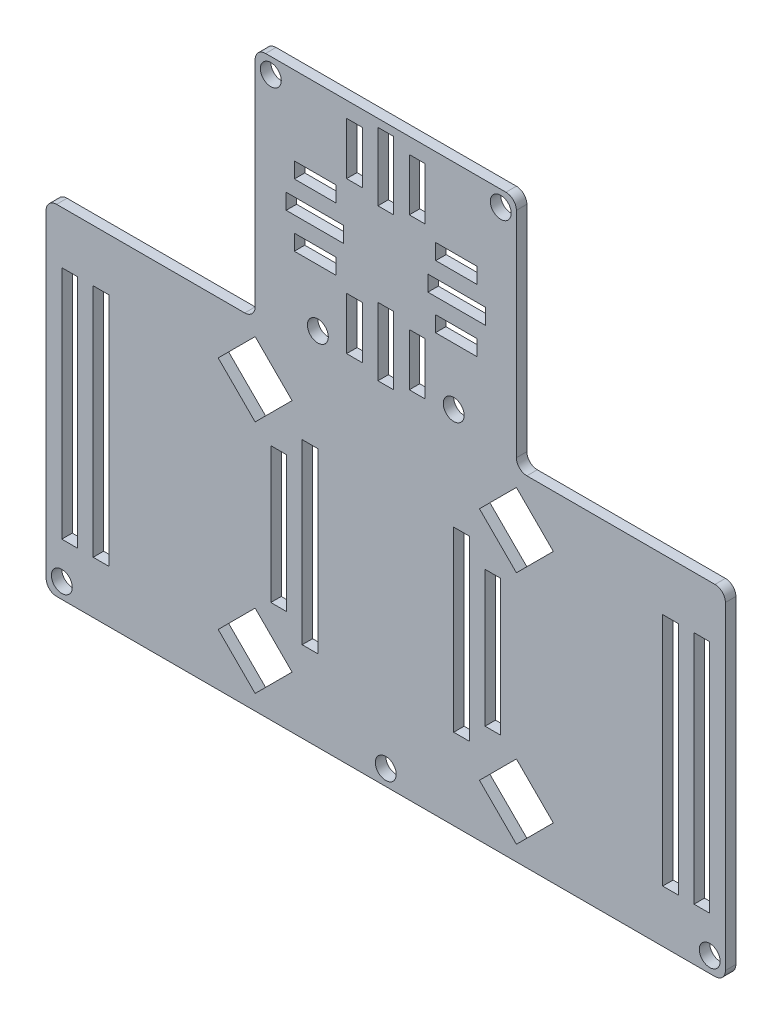
SolidWorks part; units mm, degrees
ref_plane "Front Plane" through (0, 0, 0) normal (0, 0, 1) x (1, 0, 0)
ref_plane "Top Plane" through (0, 0, 0) normal (0, 1, 0) x (1, 0, 0)
ref_plane "Right Plane" through (0, 0, 0) normal (1, 0, 0) x (0, 0, -1)
sketch "Sketch1" plane through (0, 0, 0) normal (0, 0, 1) x (1, 0, 0)
  line L1 (65, -32.5) -> (-65, -32.5)
  line L2 (65, -32.5) -> (65, 32.5)
  line L3 (65, 32.5) -> (-65, 32.5)
  line L4 (-65, -32.5) -> (-65, 32.5)
  line L5 (65, -32.5) -> (-65, 32.5) construction
  line L6 (65, 32.5) -> (-65, -32.5) construction
  line L7 (25, -12.5) -> (-25, -12.5)
  line L8 (25, -12.5) -> (25, 77.5)
  line L9 (25, 77.5) -> (-25, 77.5)
  line L10 (-25, -12.5) -> (-25, 77.5)
  line L11 (25, -12.5) -> (-25, 77.5) construction
  line L12 (25, 77.5) -> (-25, -12.5) construction
  point P0 (0, 0)
  point P6 (0, 32.5)
extrude "Boss-Extrude1" add sketch "Sketch1" along normal blind 2 contours L7 L10 L3 L4 L1 L2 L8 | L10 L3 L8 L9 | L10 L7 L8 L3
fillet "Fillet1" radius 2 8 edges at (25, 77.5, 1) (65, -32.5, 1) (65, 32.5, 1) (25, 32.5, 1) (-25, 32.5, 1) (-25, 77.5, 1) (-65, 32.5, 1) (-65, -32.5, 1)
sketch "Sketch3" plane through (0, 0, 0) normal (0, 0, -1) x (-1, 0, 0)
  line L0 (0, -32.5) -> (0, 77.5)
  line L1 (25, 55) -> (-25, 55)
  line L2 (-62, 0) -> (-62, 22.5)
  line L3 (-62, 0) -> (-62, -22.5)
  line L4 (-62, -22.5) -> (-59, -22.5)
  line L5 (-59, -22.5) -> (-59, 22.5)
  line L6 (-59, 22.5) -> (-62, 22.5)
  line L7 (-13, -17) -> (-16, -17)
  line L8 (-56, 22.5) -> (-56, -22.5)
  line L9 (-16, -17) -> (-16, 13)
  line L10 (-56, -22.5) -> (-53, -22.5)
  line L11 (-53, -22.5) -> (-53, 22.5)
  line L12 (-53, 22.5) -> (-56, 22.5)
  line L13 (-63, -32.5) -> (63, -32.5) construction
  line L14 (-23, 77.5) -> (23, 77.5) construction
  line L15 (65, -30.5) -> (65, 30.5) construction
  line L16 (65, 22.5) -> (65, -22.5)
  line L17 (25, 34.5) -> (25, 75.5) construction
  line L18 (-25, -15.4289) -> (-32.0711, -22.5)
  line L19 (-32.0711, -22.5) -> (-25, -29.5711)
  line L20 (-25, -29.5711) -> (-17.9289, -22.5)
  line L21 (-25, 34.5) -> (-25, 75.5) construction
  line L22 (-1.5, 45.5) -> (-1.5, 47)
  line L23 (-1.5, 35.5) -> (-1.5, 34)
  line L24 (-17.9289, -22.5) -> (-25, -15.4289)
  line L25 (-25, 29.5711) -> (-32.0711, 22.5)
  line L26 (-32.0711, 22.5) -> (-25, 15.4289)
  line L27 (-25, 15.4289) -> (-17.9289, 22.5)
  line L28 (-17.9289, 22.5) -> (-25, 29.5711)
  line L29 (-25, 0) -> (-22, 0)
  line L30 (-22, 0) -> (-22, 13)
  line L31 (-22, 0) -> (-22, -13)
  line L32 (-22, -13) -> (-19, -13)
  line L33 (-19, -13) -> (-19, 13)
  line L34 (-19, 13) -> (-22, 13)
  line L35 (-1.5, 34) -> (1.5, 34)
  line L36 (-16, 13) -> (-16, 17)
  line L37 (-16, 17) -> (-13, 17)
  line L38 (-13, 17) -> (-13, -17)
  line L39 (-1.5, 45.5) -> (-1.5, 35.5)
  line L40 (-1.5, 47) -> (1.5, 47)
  line L41 (-4.5, 45.5) -> (-7.5, 45.5)
  line L42 (-7.5, 35.5) -> (-4.5, 35.5)
  line L43 (-8.0637, 56.4704) -> (-8.0637, 53.4704)
  line L44 (-19.0637, 56.4704) -> (-8.0637, 56.4704)
  line L45 (-19.0637, 53.4704) -> (-8.0637, 53.4704)
  line L46 (-19.0637, 53.4704) -> (-19.0637, 56.4704)
  line L47 (-7.5, 45.5) -> (-7.5, 35.5)
  line L48 (-4.5, 45.5) -> (-4.5, 35.5)
  line L49 (-9.5637, 59.4484) -> (-17.5, 59.4484)
  line L50 (7.5, 74.5) -> (4.5, 74.5)
  line L51 (-17.5, 59.4484) -> (-17.5, 62.4484)
  line L52 (-17.5, 62.4484) -> (-9.5637, 62.4484)
  line L53 (-9.5637, 62.4484) -> (-9.5637, 59.4484)
  line L54 (7.5, 64.5) -> (7.5, 74.5)
  line L55 (-9.5087, 50.4704) -> (-17.5, 50.4704)
  line L56 (-17.5, 50.4704) -> (-17.5, 47.4704)
  line L57 (-17.5, 47.4704) -> (-9.5087, 47.4704)
  line L58 (-9.5087, 47.4704) -> (-9.5087, 50.4704)
  line L59 (1.5, 74.5) -> (1.5, 76)
  line L60 (-4.5, 64.5) -> (-7.5, 64.5)
  line L61 (-4.5, 64.5) -> (-4.5, 74.5)
  line L62 (1.5, 64.5) -> (1.5, 63)
  line L63 (1.5, 64.5) -> (1.5, 74.5)
  line L64 (-1.5, 64.5) -> (-1.5, 74.5)
  line L65 (-1.5, 64.5) -> (-1.5, 63)
  line L66 (-1.5, 74.5) -> (-1.5, 76)
  line L67 (-1.5, 63) -> (1.5, 63)
  line L68 (-1.5, 76) -> (1.5, 76)
  line L69 (-7.5, 64.5) -> (-7.5, 74.5)
  line L70 (-7.5, 74.5) -> (-4.5, 74.5)
  line L71 (4.5, 64.5) -> (4.5, 74.5)
  line L72 (4.5, 64.5) -> (7.5, 64.5)
  line L73 (9.5087, 47.4704) -> (9.5087, 50.4704)
  line L74 (17.5, 47.4704) -> (9.5087, 47.4704)
  line L75 (17.5, 50.4704) -> (17.5, 47.4704)
  line L76 (9.5087, 50.4704) -> (17.5, 50.4704)
  line L77 (9.5637, 62.4484) -> (9.5637, 59.4484)
  line L78 (17.5, 62.4484) -> (9.5637, 62.4484)
  line L79 (17.5, 59.4484) -> (17.5, 62.4484)
  line L80 (9.5637, 59.4484) -> (17.5, 59.4484)
  line L81 (4.5, 45.5) -> (4.5, 35.5)
  line L82 (7.5, 45.5) -> (7.5, 35.5)
  line L83 (19.0637, 53.4704) -> (8.0637, 53.4704)
  line L84 (19.0637, 56.4704) -> (8.0637, 56.4704)
  line L85 (8.0637, 56.4704) -> (8.0637, 53.4704)
  line L86 (7.5, 35.5) -> (4.5, 35.5)
  line L87 (4.5, 45.5) -> (7.5, 45.5)
  line L88 (1.5, 45.5) -> (1.5, 35.5)
  line L89 (1.5, 35.5) -> (1.5, 34)
  line L90 (1.5, 45.5) -> (1.5, 47)
  line L91 (13, 17) -> (13, -17)
  line L92 (16, 17) -> (13, 17)
  line L93 (16, 13) -> (16, 17)
  line L94 (19, 13) -> (22, 13)
  line L95 (19, -13) -> (19, 13)
  line L96 (22, -13) -> (19, -13)
  line L97 (22, 0) -> (22, -13)
  line L98 (22, 0) -> (22, 13)
  line L99 (25, 0) -> (22, 0)
  line L100 (17.9289, 22.5) -> (25, 29.5711)
  line L101 (25, 15.4289) -> (17.9289, 22.5)
  line L102 (32.0711, 22.5) -> (25, 15.4289)
  line L103 (25, 29.5711) -> (32.0711, 22.5)
  line L104 (17.9289, -22.5) -> (25, -15.4289)
  line L105 (25, -29.5711) -> (17.9289, -22.5)
  line L106 (32.0711, -22.5) -> (25, -29.5711)
  line L107 (25, -15.4289) -> (32.0711, -22.5)
  line L108 (53, 22.5) -> (56, 22.5)
  line L109 (53, -22.5) -> (53, 22.5)
  line L110 (56, -22.5) -> (53, -22.5)
  line L111 (16, -17) -> (16, 13)
  line L112 (56, 22.5) -> (56, -22.5)
  line L113 (13, -17) -> (16, -17)
  line L114 (59, 22.5) -> (62, 22.5)
  line L115 (59, -22.5) -> (59, 22.5)
  line L116 (62, -22.5) -> (59, -22.5)
  line L117 (62, 0) -> (62, -22.5)
  line L118 (62, 0) -> (62, 22.5)
  line L119 (19.0637, 53.4704) -> (19.0637, 56.4704)
  point P66 (0, 76)
  point P74 (0, 63)
  point P102 (0, 47)
  point P105 (0, 34)
extrude "Cut-Extrude1" cut sketch "Sketch3" against normal blind 2 contours L87 L81 L86 L82 | L48 L41 L47 L42 | L40 L22 L39 L23 L35 L0 | L88 L90 L40 L0 L35 L89 | L70 L69 L60 L61 | L68 L66 L64 L65 L67 L0 | L68 L0 L67 L62 L63 L59 | L71 L72 L54 L50 | L77 L80 L79 L78 | L1 L119 L84 L85 | L83 L119 L1 L85 | L76 L73 L74 L75 | L53 L52 L51 L49 | L46 L1 L43 L44 | L46 L45 L43 L1 | L57 L58 L55 L56 | L27 L28 L25 L26 | L33 L34 L30 L31 L32 | L38 L37 L36 L9 L7 | L20 L24 L18 L19 | L11 L12 L8 L10 | L5 L6 L2 L3 L4 | L103 L100 L101 L102 | L97 L98 L94 L95 L96 | L91 L113 L111 L93 L92 | L107 L104 L105 L106 | L117 L118 L114 L115 L116 | L112 L108 L109 L110
sketch "Sketch4" plane through (0, 0, 2) normal (0, 0, 1) x (1, 0, 0)
  line L0 (0, -32.5) -> (0, -29.5)
  line L1 (63, -32.5) -> (-63, -32.5) construction
  line L2 (0, -29.5) -> (0, 36.5)
  line L3 (0, 36.5) -> (13, 36.5)
  line L4 (0, 36.5) -> (-13, 36.5)
  line L5 (0, -29.5) -> (-62, -29.5)
  line L6 (0, -29.5) -> (62, -29.5)
  line L7 (0, 77.5) -> (0, 74.5)
  line L8 (23, 77.5) -> (-23, 77.5) construction
  line L9 (0, 74.5) -> (22, 74.5)
  line L10 (0, 74.5) -> (-22, 74.5)
  circle A0 centre (-13, 36.5) radius 2
  circle A1 centre (13, 36.5) radius 2
  circle A2 centre (0, -29.5) radius 2
  circle A3 centre (-62, -29.5) radius 2
  circle A4 centre (62, -29.5) radius 2
  circle A5 centre (-22, 74.5) radius 2
  circle A6 centre (22, 74.5) radius 2
extrude "Cut-Extrude2" cut sketch "Sketch4" against normal blind 10
sketch "Sketch5" plane through (0, 0, 0) normal (0, 0, -1) x (-1, 0, 0)
  line L0 (0, -29.5) -> (-62, -29.5)
  line L1 (13, 36.5) -> (-13, 36.5)
  line L2 (0, 36.5) -> (0, -29.5)
  line L3 (22, 74.5) -> (-22, 74.5)
  line L4 (0, 36.5) -> (0, 74.5)
  line L5 (62, -29.5) -> (0, -29.5)
